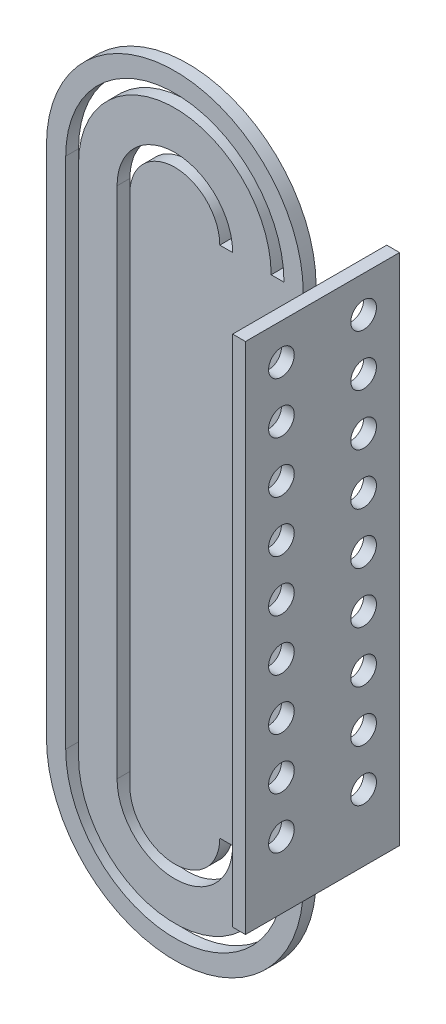
SolidWorks part; units mm, degrees
ref_plane "Front Plane" through (0, 0, 0) normal (0, 0, 1) x (1, 0, 0)
ref_plane "Top Plane" through (0, 0, 0) normal (0, 1, 0) x (1, 0, 0)
ref_plane "Right Plane" through (0, 0, 0) normal (1, 0, 0) x (0, 0, -1)
sketch "Side Profile Sketch" plane through (0, 0, 0) normal (0, 0, 1) x (1, 0, 0)
  line L0 (0, 0) -> (0, 508) construction
  line L1 (0, 0) -> (0, 508) construction
  line L2 (-127, 0) -> (-127, 508)
  line L3 (127, 0) -> (127, 508)
  line L4 (-127, 508) -> (127, 508) construction
  line L5 (-127, 0) -> (127, 0) construction
  arc A0 (-127, 0) -> (127, 0) centre (0, 0) ccw
  arc A1 (127, 508) -> (-127, 508) centre (0, 508) ccw
  point P3 (0, 254)
  dimension "D3" = 508
  dimension "D1" = 508
  dimension "D2" = 254
extrude "Side Profile Extrude" add sketch "Side Profile Sketch" along normal mid plane 12.7
sketch "Mounting Bracket Profile Sketch" plane through (127, 0, 0) normal (1, 0, 0) x (0, 0, -1)
  line L0 (-6.35, 508) -> (6.35, 508) construction
  line L1 (-76.2, 508) -> (76.2, 508)
  line L2 (-76.2, 508) -> (-76.2, 0)
  line L3 (-76.2, 0) -> (76.2, 0)
  line L4 (76.2, 508) -> (76.2, 0)
  line L7 (-6.35, 0) -> (6.35, 0) construction
  point P12 (0, 0)
  point P13 (0, 0)
  dimension "D1" = 152.4
extrude "Mounting Bracket Profile Extrude" add sketch "Mounting Bracket Profile Sketch" along normal blind 12.7
sketch "Mounting Bracket Holes Sketch" plane through (139.7, 0, 0) normal (1, 0, 0) x (0, 0, -1)
  line L0 (-76.2, 508) -> (-76.2, 0) construction
  line L1 (76.2, 508) -> (-76.2, 508) construction
  line L2 (0, 146.685) -> (0, -146.685) construction
  circle A0 centre (-40.64, 472.44) radius 12.7
  circle A1 centre (-40.64, 421.64) radius 12.7
  circle A2 centre (-40.64, 370.84) radius 12.7
  circle A3 centre (-40.64, 320.04) radius 12.7
  circle A4 centre (-40.64, 269.24) radius 12.7
  circle A5 centre (-40.64, 218.44) radius 12.7
  circle A6 centre (-40.64, 167.64) radius 12.7
  circle A7 centre (-40.64, 116.84) radius 12.7
  circle A8 centre (-40.64, 66.04) radius 12.7
  circle A9 centre (40.64, 66.04) radius 12.7
  circle A10 centre (40.64, 116.84) radius 12.7
  circle A11 centre (40.64, 167.64) radius 12.7
  circle A12 centre (40.64, 218.44) radius 12.7
  circle A13 centre (40.64, 269.24) radius 12.7
  circle A14 centre (40.64, 320.04) radius 12.7
  circle A15 centre (40.64, 370.84) radius 12.7
  circle A16 centre (40.64, 421.64) radius 12.7
  circle A17 centre (40.64, 472.44) radius 12.7
  dimension "D1" = 25.4
  dimension "D2" = 35.56
  dimension "D3" = 35.56
  dimension "D4" = 9
extrude "Mounting Bracket Holes Cut" cut sketch "Mounting Bracket Holes Sketch" against normal up to surface (12.7 mm away) up to face at (127, 254, 41.275)
sketch "Outer Track Sketch" plane through (0, 0, 6.35) normal (0, 0, 1) x (1, 0, 0)
  line L0 (0, 0) -> (0, 508) construction
  line L1 (-101.6, 0) -> (-101.6, 508) construction
  line L2 (101.6, 0) -> (101.6, 508) construction
  line L3 (-107.95, 0) -> (-107.95, 508)
  line L5 (-95.25, 0) -> (-95.25, 508)
  line L7 (95.25, 508) -> (107.95, 508)
  line L8 (-127, 508) -> (127, 508) construction
  line L9 (95.25, 0) -> (107.95, 0)
  line L10 (-127, 0) -> (127, 0) construction
  line L11 (95.25, 0) -> (95.25, 508) construction
  line L12 (107.95, 0) -> (107.95, 508) construction
  arc A0 (-101.6, 0) -> (101.6, 0) centre (0, 0) ccw construction
  arc A1 (101.6, 508) -> (-101.6, 508) centre (0, 508) ccw construction
  arc A2 (107.95, 508) -> (-107.95, 508) centre (0, 508) ccw
  arc A3 (-107.95, 0) -> (107.95, 0) centre (0, 0) ccw
  arc A4 (95.25, 508) -> (-95.25, 508) centre (0, 508) ccw
  arc A5 (-95.25, 0) -> (95.25, 0) centre (0, 0) ccw
  point P4 (0, 254)
  dimension "D1" = 203.2
  dimension "D2" = 6.35
  dimension "D3" = 6.35
extrude "Outer Track Cut" cut sketch "Outer Track Sketch" against normal up to surface (12.7 mm away) up to face at (0, 254, -6.35)
sketch "Inner Track Sketch" plane through (0, 0, 6.35) normal (0, 0, 1) x (1, 0, 0)
  line L0 (0, 0) -> (0, 508) construction
  line L1 (-50.8, 0) -> (-50.8, 508) construction
  line L2 (50.8, 0) -> (50.8, 508) construction
  line L3 (-101.6, 0) -> (-101.6, 508) construction
  line L4 (-57.15, 0) -> (-57.15, 508)
  line L6 (-44.45, 0) -> (-44.45, 508)
  line L8 (44.45, 508) -> (57.15, 508)
  line L9 (44.45, 0) -> (57.15, 0)
  line L10 (57.15, 0) -> (57.15, 508) construction
  line L11 (44.45, 0) -> (44.45, 508) construction
  arc A0 (-50.8, 0) -> (50.8, 0) centre (0, 0) ccw construction
  arc A1 (50.8, 508) -> (-50.8, 508) centre (0, 508) ccw construction
  arc A2 (57.15, 508) -> (-57.15, 508) centre (0, 508) ccw
  arc A3 (-57.15, 0) -> (57.15, 0) centre (0, 0) ccw
  arc A4 (44.45, 508) -> (-44.45, 508) centre (0, 508) ccw
  arc A5 (-44.45, 0) -> (44.45, 0) centre (0, 0) ccw
  point P4 (0, 254)
  point P23 (0, 0)
  dimension "D2" = 6.35
  dimension "D1" = 50.8
  dimension "D3" = 6.35
extrude "Inner Track Cut" cut sketch "Inner Track Sketch" against normal up to surface (12.7 mm away) up to face at (0, 254, -6.35)
